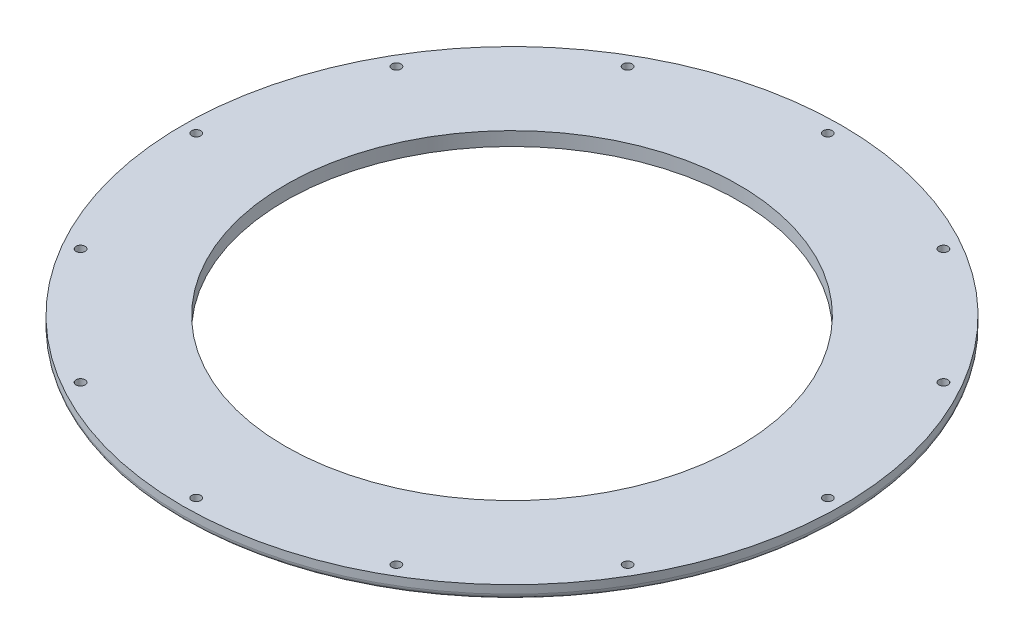
SolidWorks part; units mm, degrees
ref_plane "前视基准面" through (0, 0, 0) normal (0, 0, 1) x (1, 0, 0)
ref_plane "上视基准面" through (0, 0, 0) normal (0, 1, 0) x (1, 0, 0)
ref_plane "右视基准面" through (0, 0, 0) normal (1, 0, 0) x (0, 0, -1)
other "Configuration Table"
sketch "草图1" plane through (0, 0, 0) normal (0, 1, 0) x (1, 0, 0)
  circle A0 centre (0, 0) radius 120
  circle A1 centre (0, 0) radius 82.5
  dimension "D1" = 240
  dimension "D2" = 165
extrude "凸台-拉伸1" add sketch "草图1" along normal blind 5
fillet "圆角1" radius 2 1 edges at (0, 0, 120)
sketch "草图2" plane through (0, 0, 0) normal (0, -1, 0) x (-1, 0, 0)
  circle A0 centre (0, 0) radius 115 construction
  circle A1 centre (0, -115) radius 1.65
  circle A2 centre (-57.5, -99.5929) radius 1.65
  circle A3 centre (-99.5929, -57.5) radius 1.65
  circle A4 centre (-115, 0) radius 1.65
  circle A5 centre (-99.5929, 57.5) radius 1.65
  circle A6 centre (-57.5, 99.5929) radius 1.65
  circle A7 centre (0, 115) radius 1.65
  circle A8 centre (57.5, 99.5929) radius 1.65
  circle A9 centre (99.5929, 57.5) radius 1.65
  circle A10 centre (115, 0) radius 1.65
  circle A11 centre (99.5929, -57.5) radius 1.65
  circle A12 centre (57.5, -99.5929) radius 1.65
  point P30 (0, 0)
  dimension "D1" = 3.3
  dimension "D2" = 12
extrude "切除-拉伸1" cut sketch "草图2" against normal blind 8
